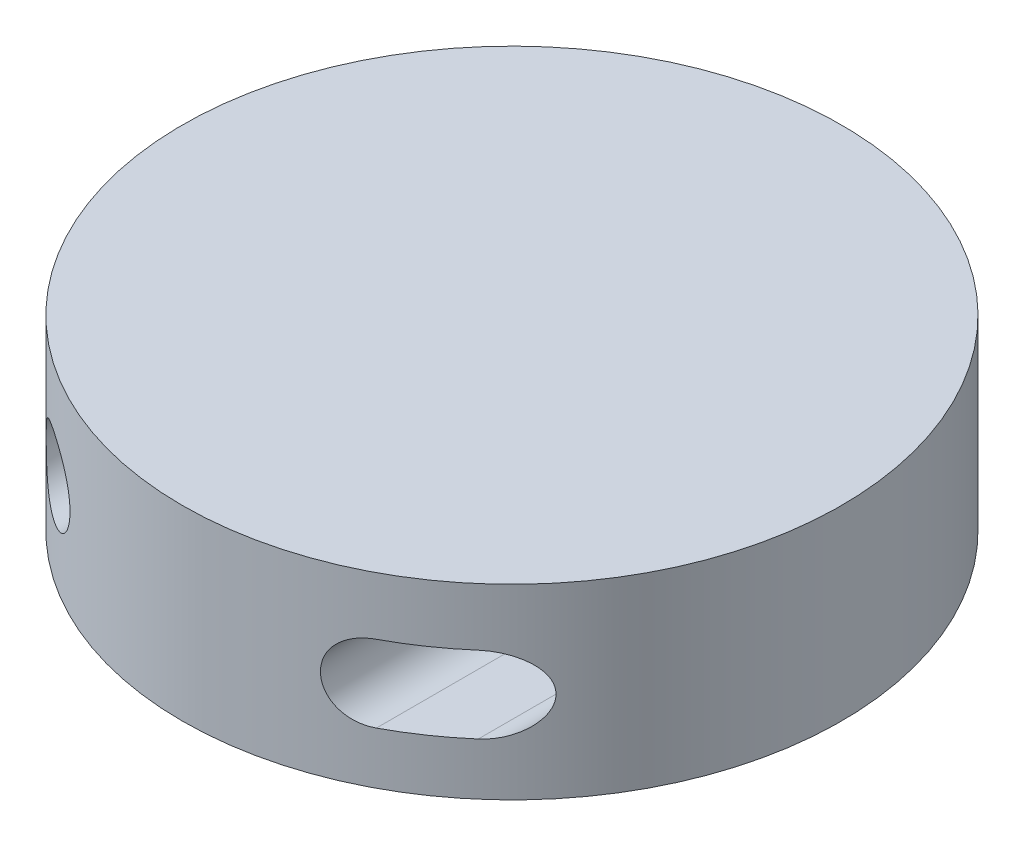
SolidWorks part; units mm, degrees
ref_plane "Front Plane" through (0, 0, 0) normal (0, 0, 1) x (1, 0, 0)
ref_plane "Top Plane" through (0, 0, 0) normal (0, 1, 0) x (1, 0, 0)
ref_plane "Right Plane" through (0, 0, 0) normal (1, 0, 0) x (0, 0, -1)
sketch "Sketch1" plane through (0, 0, 0) normal (0, 1, 0) x (1, 0, 0)
  circle A0 centre (0, 0) radius 30
  dimension "D1" = 60
extrude "Boss-Extrude1" add sketch "Sketch1" along normal blind 17
ref_plane "Plane1" through (0, 0, 30) normal (0, 0, 1) x (1, 0, 0)
sketch "Sketch2" plane through (0, 0, 30) normal (0, 0, 1) x (1, 0, 0)
  line L0 (0, 16.5) -> (0, 0) construction
  line L1 (-16.875, 8.25) -> (16.875, 8.25) construction
  line L4 (14.125, 8.25) -> (19.625, 8.25) construction
  line L5 (14.125, 11.75) -> (19.625, 11.75)
  line L6 (14.125, 4.75) -> (19.625, 4.75)
  circle A0 centre (-16.875, 8.25) radius 3.5
  arc A1 (14.125, 11.75) -> (14.125, 4.75) centre (14.125, 8.25) ccw
  arc A2 (19.625, 4.75) -> (19.625, 11.75) centre (19.625, 8.25) ccw
  point P7 (0, 8.25)
  point P8 (0, 8.25)
  point P13 (16.875, 8.25)
  dimension "D2" = 7
  dimension "D3" = 3.5
  dimension "D1" = 16.5
  dimension "D4" = 5.5
  dimension "D5" = 33.75
extrude "Cut-Extrude1" cut sketch "Sketch2" against normal blind 16.5
sketch "Sketch3" plane through (0, 0, 0) normal (0, -1, 0) x (1, 0, 0)
  circle A0 centre (0, 0) radius 10
  dimension "D1" = 20
extrude "Boss-Extrude2" add sketch "Sketch3" along normal blind 1
